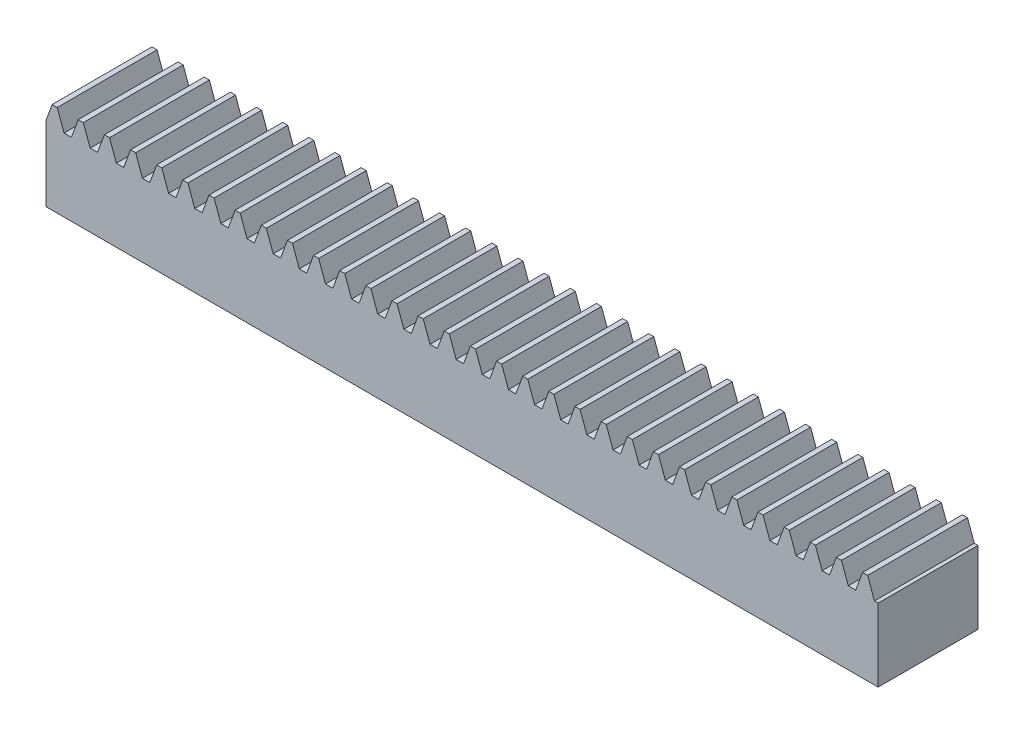
SolidWorks part; units mm, degrees
ref_plane "Front Plane" through (0, 0, 0) normal (0, 0, 1) x (1, 0, 0)
ref_plane "Top Plane" through (0, 0, 0) normal (0, 1, 0) x (1, 0, 0)
ref_plane "Right Plane" through (0, 0, 0) normal (1, 0, 0) x (0, 0, -1)
sketch "Sketch1" plane through (0, 0, 0) normal (0, 0, 1) x (1, 0, 0)
  line L0 (-49.2676, 5.5) -> (-50, 3.4877)
  line L1 (-50, 3.4877) -> (-50, -5.5)
  line L2 (-50, -5.5) -> (50, -5.5)
  line L3 (50, -5.5) -> (50, 3.25)
  line L4 (50, 3.25) -> (49.5556, 3.25)
  line L5 (49.5556, 3.25) -> (48.7366, 5.5)
  line L6 (48.7366, 5.5) -> (48.1218, 5.5)
  line L7 (48.1218, 5.5) -> (47.3028, 3.25)
  line L8 (47.3028, 3.25) -> (46.414, 3.25)
  line L9 (46.414, 3.25) -> (45.595, 5.5)
  line L10 (45.595, 5.5) -> (44.9802, 5.5)
  line L11 (44.9802, 5.5) -> (44.1613, 3.25)
  line L12 (44.1613, 3.25) -> (43.2724, 3.25)
  line L13 (43.2724, 3.25) -> (42.4534, 5.5)
  line L14 (42.4534, 5.5) -> (41.8386, 5.5)
  line L15 (41.8386, 5.5) -> (41.0197, 3.25)
  line L16 (41.0197, 3.25) -> (40.1308, 3.25)
  line L17 (40.1308, 3.25) -> (39.3119, 5.5)
  line L18 (39.3119, 5.5) -> (38.697, 5.5)
  line L19 (38.697, 5.5) -> (37.8781, 3.25)
  line L20 (37.8781, 3.25) -> (36.9892, 3.25)
  line L21 (36.9892, 3.25) -> (36.1703, 5.5)
  line L22 (36.1703, 5.5) -> (35.5554, 5.5)
  line L23 (35.5554, 5.5) -> (34.7365, 3.25)
  line L24 (34.7365, 3.25) -> (33.8476, 3.25)
  line L25 (33.8476, 3.25) -> (33.0287, 5.5)
  line L26 (33.0287, 5.5) -> (32.4138, 5.5)
  line L27 (32.4138, 5.5) -> (31.5949, 3.25)
  line L28 (31.5949, 3.25) -> (30.706, 3.25)
  line L29 (30.706, 3.25) -> (29.8871, 5.5)
  line L30 (29.8871, 5.5) -> (29.2722, 5.5)
  line L31 (29.2722, 5.5) -> (28.4533, 3.25)
  line L32 (28.4533, 3.25) -> (27.5644, 3.25)
  line L33 (27.5644, 3.25) -> (26.7455, 5.5)
  line L34 (26.7455, 5.5) -> (26.1306, 5.5)
  line L35 (26.1306, 5.5) -> (25.3117, 3.25)
  line L36 (25.3117, 3.25) -> (24.4228, 3.25)
  line L37 (24.4228, 3.25) -> (23.6039, 5.5)
  line L38 (23.6039, 5.5) -> (22.989, 5.5)
  line L39 (22.989, 5.5) -> (22.1701, 3.25)
  line L40 (22.1701, 3.25) -> (21.2812, 3.25)
  line L41 (21.2812, 3.25) -> (20.4623, 5.5)
  line L42 (20.4623, 5.5) -> (19.8474, 5.5)
  line L43 (19.8474, 5.5) -> (19.0285, 3.25)
  line L44 (19.0285, 3.25) -> (18.1396, 3.25)
  line L45 (18.1396, 3.25) -> (17.3207, 5.5)
  line L46 (17.3207, 5.5) -> (16.7058, 5.5)
  line L47 (16.7058, 5.5) -> (15.8869, 3.25)
  line L48 (15.8869, 3.25) -> (14.998, 3.25)
  line L49 (14.998, 3.25) -> (14.1791, 5.5)
  line L50 (14.1791, 5.5) -> (13.5643, 5.5)
  line L51 (13.5643, 5.5) -> (12.7453, 3.25)
  line L52 (12.7453, 3.25) -> (11.8565, 3.25)
  line L53 (11.8565, 3.25) -> (11.0375, 5.5)
  line L54 (11.0375, 5.5) -> (10.4227, 5.5)
  line L55 (10.4227, 5.5) -> (9.6037, 3.25)
  line L56 (9.6037, 3.25) -> (8.7149, 3.25)
  line L57 (8.7149, 3.25) -> (7.8959, 5.5)
  line L58 (7.8959, 5.5) -> (7.2811, 5.5)
  line L59 (7.2811, 5.5) -> (6.4621, 3.25)
  line L60 (6.4621, 3.25) -> (5.5733, 3.25)
  line L61 (5.5733, 3.25) -> (4.7543, 5.5)
  line L62 (4.7543, 5.5) -> (4.1395, 5.5)
  line L63 (4.1395, 5.5) -> (3.3205, 3.25)
  line L64 (3.3205, 3.25) -> (2.4317, 3.25)
  line L65 (2.4317, 3.25) -> (1.6127, 5.5)
  line L66 (1.6127, 5.5) -> (0.9979, 5.5)
  line L67 (0.9979, 5.5) -> (0.179, 3.25)
  line L68 (0.179, 3.25) -> (-0.7099, 3.25)
  line L69 (-0.7099, 3.25) -> (-1.5289, 5.5)
  line L70 (-1.5289, 5.5) -> (-2.1437, 5.5)
  line L71 (-2.1437, 5.5) -> (-2.9626, 3.25)
  line L72 (-2.9626, 3.25) -> (-3.8515, 3.25)
  line L73 (-3.8515, 3.25) -> (-4.6704, 5.5)
  line L74 (-4.6704, 5.5) -> (-5.2853, 5.5)
  line L75 (-5.2853, 5.5) -> (-6.1042, 3.25)
  line L76 (-6.1042, 3.25) -> (-6.9931, 3.25)
  line L77 (-6.9931, 3.25) -> (-7.812, 5.5)
  line L78 (-7.812, 5.5) -> (-8.4269, 5.5)
  line L79 (-8.4269, 5.5) -> (-9.2458, 3.25)
  line L80 (-9.2458, 3.25) -> (-10.1347, 3.25)
  line L81 (-10.1347, 3.25) -> (-10.9536, 5.5)
  line L82 (-10.9536, 5.5) -> (-11.5685, 5.5)
  line L83 (-11.5685, 5.5) -> (-12.3874, 3.25)
  line L84 (-12.3874, 3.25) -> (-13.2763, 3.25)
  line L85 (-13.2763, 3.25) -> (-14.0952, 5.5)
  line L86 (-14.0952, 5.5) -> (-14.7101, 5.5)
  line L87 (-14.7101, 5.5) -> (-15.529, 3.25)
  line L88 (-15.529, 3.25) -> (-16.4179, 3.25)
  line L89 (-16.4179, 3.25) -> (-17.2368, 5.5)
  line L90 (-17.2368, 5.5) -> (-17.8517, 5.5)
  line L91 (-17.8517, 5.5) -> (-18.6706, 3.25)
  line L92 (-18.6706, 3.25) -> (-19.5595, 3.25)
  line L93 (-19.5595, 3.25) -> (-20.3784, 5.5)
  line L94 (-20.3784, 5.5) -> (-20.9933, 5.5)
  line L95 (-20.9933, 5.5) -> (-21.8122, 3.25)
  line L96 (-21.8122, 3.25) -> (-22.7011, 3.25)
  line L97 (-22.7011, 3.25) -> (-23.52, 5.5)
  line L98 (-23.52, 5.5) -> (-24.1349, 5.5)
  line L99 (-24.1349, 5.5) -> (-24.9538, 3.25)
  line L100 (-24.9538, 3.25) -> (-25.8427, 3.25)
  line L101 (-25.8427, 3.25) -> (-26.6616, 5.5)
  line L102 (-26.6616, 5.5) -> (-27.2764, 5.5)
  line L103 (-27.2764, 5.5) -> (-28.0954, 3.25)
  line L104 (-28.0954, 3.25) -> (-28.9843, 3.25)
  line L105 (-28.9843, 3.25) -> (-29.8032, 5.5)
  line L106 (-29.8032, 5.5) -> (-30.418, 5.5)
  line L107 (-30.418, 5.5) -> (-31.237, 3.25)
  line L108 (-31.237, 3.25) -> (-32.1258, 3.25)
  line L109 (-32.1258, 3.25) -> (-32.9448, 5.5)
  line L110 (-32.9448, 5.5) -> (-33.5596, 5.5)
  line L111 (-33.5596, 5.5) -> (-34.3786, 3.25)
  line L112 (-34.3786, 3.25) -> (-35.2674, 3.25)
  line L113 (-35.2674, 3.25) -> (-36.0864, 5.5)
  line L114 (-36.0864, 5.5) -> (-36.7012, 5.5)
  line L115 (-36.7012, 5.5) -> (-37.5202, 3.25)
  line L116 (-37.5202, 3.25) -> (-38.409, 3.25)
  line L117 (-38.409, 3.25) -> (-39.228, 5.5)
  line L118 (-39.228, 5.5) -> (-39.8428, 5.5)
  line L119 (-39.8428, 5.5) -> (-40.6618, 3.25)
  line L120 (-40.6618, 3.25) -> (-41.5506, 3.25)
  line L121 (-41.5506, 3.25) -> (-42.3696, 5.5)
  line L122 (-42.3696, 5.5) -> (-42.9844, 5.5)
  line L123 (-42.9844, 5.5) -> (-43.8033, 3.25)
  line L124 (-43.8033, 3.25) -> (-44.6922, 3.25)
  line L125 (-44.6922, 3.25) -> (-45.5111, 5.5)
  line L126 (-45.5111, 5.5) -> (-46.126, 5.5)
  line L127 (-46.126, 5.5) -> (-46.9449, 3.25)
  line L128 (-46.9449, 3.25) -> (-47.8338, 3.25)
  line L129 (-47.8338, 3.25) -> (-48.6527, 5.5)
  line L130 (-48.6527, 5.5) -> (-49.2676, 5.5)
extrude "Boss-Extrude1" add sketch "Sketch1" along normal blind 12
